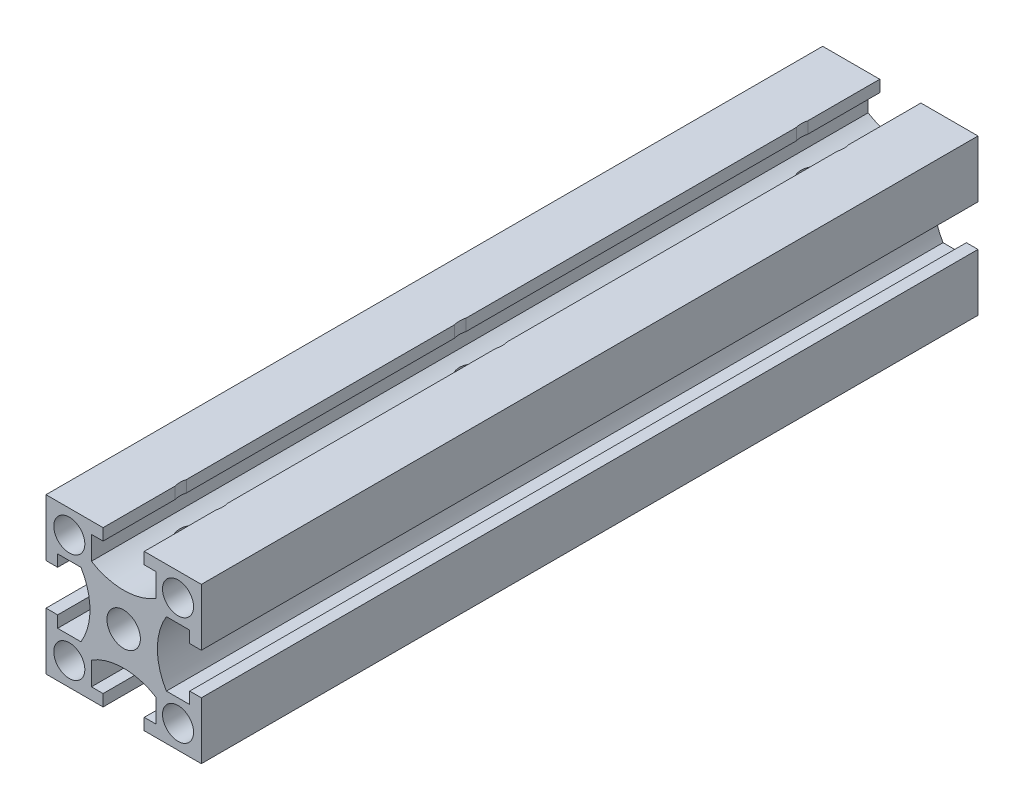
SolidWorks part; units mm, degrees
material "6061-T6 (SS)"
ref_plane "정면" through (0, 0, 0) normal (0, 0, 1) x (1, 0, 0)
ref_plane "윗면" through (0, 0, 0) normal (0, 1, 0) x (1, 0, 0)
ref_plane "우측면" through (0, 0, 0) normal (1, 0, 0) x (0, 0, -1)
sketch "스케치1" plane through (0, 0, 0) normal (0, 0, 1) x (1, 0, 0)
  line L1 (-10, 10) -> (10, 10)
  line L2 (-10, 10) -> (-10, -10)
  line L3 (-10, -10) -> (10, -10)
  line L4 (10, 10) -> (10, -10)
  line L5 (-10, 10) -> (10, -10) construction
  line L6 (-10, -10) -> (10, 10) construction
  point P0 (0, 0)
  dimension "D1" = 20
  dimension "D2" = 20
extrude "보스-돌출1" add sketch "스케치1" along normal blind 100
sketch "스케치2" plane through (0, 0, 100) normal (0, 0, 1) x (1, 0, 0)
  line L0 (-2.65, 10) -> (-2.65, 8.5)
  line L1 (10, 10) -> (-10, 10) construction
  line L2 (-2.65, 8.5) -> (-4.15, 8.5)
  line L3 (-4.15, 8.5) -> (-4.15, 5.5)
  line L4 (-2.65, 10) -> (2.65, 10)
  line L5 (2.65, 10) -> (2.65, 8.5)
  line L6 (2.65, 8.5) -> (4.15, 8.5)
  line L7 (4.15, 8.5) -> (4.15, 5.5)
  line L8 (10, 2.65) -> (8.5, 2.65)
  line L9 (8.5, 2.65) -> (8.5, 4.15)
  line L10 (8.5, 4.15) -> (5.5, 4.15)
  line L11 (10, 2.65) -> (10, -2.65)
  line L12 (10, -2.65) -> (8.5, -2.65)
  line L13 (8.5, -2.65) -> (8.5, -4.15)
  line L14 (8.5, -4.15) -> (5.5, -4.15)
  line L15 (2.65, -10) -> (2.65, -8.5)
  line L16 (2.65, -8.5) -> (4.15, -8.5)
  line L17 (4.15, -8.5) -> (4.15, -5.5)
  line L18 (2.65, -10) -> (-2.65, -10)
  line L19 (-2.65, -10) -> (-2.65, -8.5)
  line L20 (-2.65, -8.5) -> (-4.15, -8.5)
  line L21 (-4.15, -8.5) -> (-4.15, -5.5)
  line L22 (-10, -2.65) -> (-8.5, -2.65)
  line L23 (-8.5, -2.65) -> (-8.5, -4.15)
  line L24 (-8.5, -4.15) -> (-5.5, -4.15)
  line L25 (-10, -2.65) -> (-10, 2.65)
  line L26 (-10, 2.65) -> (-8.5, 2.65)
  line L27 (-8.5, 2.65) -> (-8.5, 4.15)
  line L28 (-8.5, 4.15) -> (-5.5, 4.15)
  arc A1 (-4.15, 5.5) -> (4.15, 5.5) centre (0, 12.3394) ccw
  arc A2 (5.5, 4.15) -> (5.5, -4.15) centre (12.3394, 0) ccw
  arc A3 (4.15, -5.5) -> (-4.15, -5.5) centre (0, -12.3394) ccw
  arc A4 (-5.5, -4.15) -> (-5.5, 4.15) centre (-12.3394, 0) ccw
  circle A5 centre (0, 0) radius 2.15
  circle A6 centre (-7, 7) radius 2
  circle A7 centre (7, 7) radius 2
  circle A8 centre (7, -7) radius 2
  circle A9 centre (-7, -7) radius 2
  point P4 (-2.65, 9.25)
  point P43 (0, 0)
  dimension "D2" = 1.5
  dimension "D8" = 4.3
  dimension "D9" = 4
  dimension "D10" = 4
  dimension "D11" = 4
  dimension "D12" = 4
  dimension "D21" = 8
  dimension "D1" = 5.3
  dimension "D3" = 8.3
  dimension "D4" = 4.15
  dimension "D5" = 2.65
  dimension "D6" = 4
  dimension "D7" = 3
  dimension "D13" = 14
  dimension "D14" = 7
  dimension "D15" = 7
  dimension "D16" = 7
  dimension "D17" = 14
  dimension "D18" = 7
  dimension "D19" = 7
  dimension "D20" = 7
extrude "컷-돌출1" cut sketch "스케치2" against normal blind 300
sketch "스케치3" plane through (-10, 0, 0) normal (-1, 0, 0) x (0, 0, 1)
  line L0 (38.2997, 7.1444) -> (60.1472, 7.1444) construction
hole_wizard "M5 여유 구멍1" positions "스케치4" profile "스케치5" hole size "M5" standard "KS" end condition through all
sketch "스케치4" plane through (0, 10, 0) normal (0, 1, 0) x (1, 0, 0)
  line L0 (-10, -100) -> (-10, 0) construction
  line L2 (10, -100) -> (10, 0) construction
  line L3 (-2.65, 0) -> (-10, 0) construction
  point P0 (0, -10)
  point P2 (0, -90)
  point P10 (0, -54)
  dimension "D1" = 10
  dimension "D2" = 10
  dimension "D3" = 10
  dimension "D4" = 10
  dimension "D5" = 54
  dimension "D6" = 10
sketch "스케치5" plane through (0, 10, 10) normal (1, 0, 0) x (0, 0, 1)
  line L0 (0, 0) -> (0, 20)
  line L1 (0, 20) -> (2.75, 20)
  line L2 (2.75, 20) -> (2.75, 0)
  line L5 (2.75, 0) -> (0, 0)
  line L11 (0, -6.35) -> (0, 107.95) construction
  dimension "관통 구멍 지름" = 5.5
  dimension "관통 구멍 깊이" = 20
